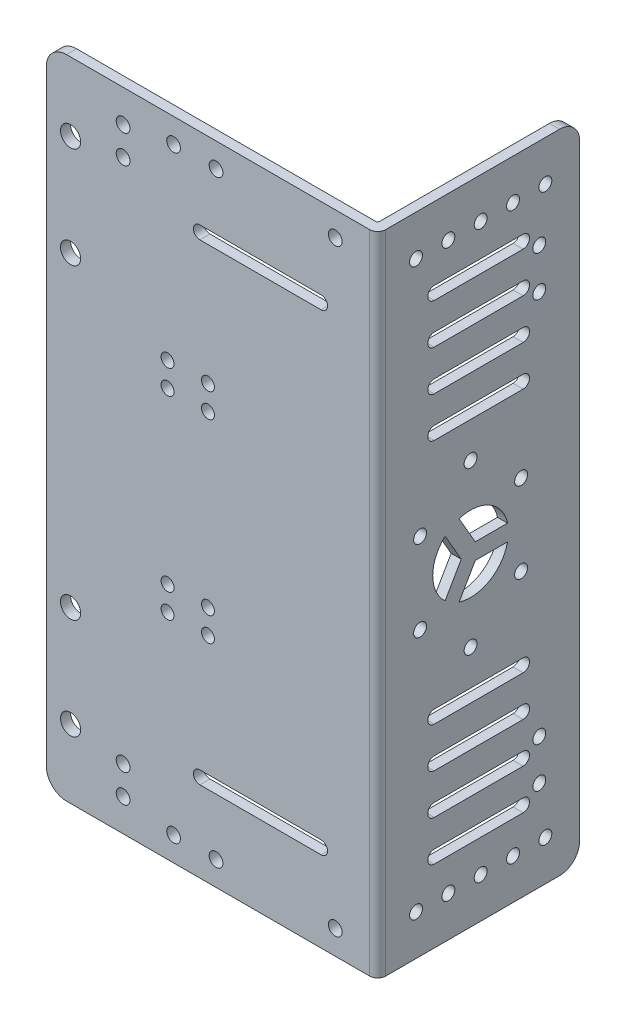
SolidWorks part; units mm, degrees
ref_plane "前视基准面" through (0, 0, 0) normal (0, 0, 1) x (1, 0, 0)
ref_plane "上视基准面" through (0, 0, 0) normal (0, 1, 0) x (1, 0, 0)
ref_plane "右视基准面" through (0, 0, 0) normal (1, 0, 0) x (0, 0, -1)
ref_plane "基准面4" through (0, 0, -50) normal (0, 0, -1) x (-1, 0, 0)
sketch "草图1" plane through (0, 0, -50) normal (0, 0, -1) x (-1, 0, 0)
  line L0 (-82, 0) -> (0, 0)
  line L1 (0, 0) -> (0, 160)
  line L2 (0, 160) -> (-82, 160)
  line L3 (-82, 160) -> (-82, 0)
extrude "凸台-拉伸1" add sketch "草图1" against normal blind 50
sketch "草图2" plane through (0, 160, 0) normal (0, 1, 0) x (-1, 0, 0)
  line L0 (0, -50) -> (0, -2.5)
  line L1 (0, -2.5) -> (-79.5, -2.5)
  line L2 (-79.5, -2.5) -> (-79.5, -50)
  line L3 (-79.5, -50) -> (0, -50)
extrude "切除-拉伸1" cut sketch "草图2" against normal through all
sketch "草图7" plane through (0, 0, -2.5) normal (0, 0, -1) x (-1, 0, 0)
  line L0 (-68, 20) -> (-38, 20)
  line L1 (-38, 23.2) -> (-68, 23.2)
  arc A0 (-68, 23.2) -> (-68, 20) centre (-68, 21.6) ccw
  arc A1 (-38, 20) -> (-38, 23.2) centre (-38, 21.6) ccw
extrude "切除-拉伸6" cut sketch "草图7" against normal through all
sketch "草图10" plane through (82, 0, 0) normal (1, 0, 0) x (0, 0, -1)
  line L0 (20.6906, 80) -> (16.6906, 86.9282)
  line L1 (16.6906, 73.0718) -> (20.6906, 80)
  arc A0 (16.6906, 86.9282) -> (16.6906, 73.0718) centre (23, 80) ccw
extrude "切除-拉伸9" cut sketch "草图10" against normal through all
sketch "草图11" plane through (82, 0, 0) normal (1, 0, 0) x (0, 0, -1)
  line L0 (20.1547, 88.9282) -> (24.1547, 82)
  line L1 (24.1547, 82) -> (32.1547, 82)
  arc A0 (32.1547, 82) -> (20.1547, 88.9282) centre (23, 80) ccw
extrude "切除-拉伸10" cut sketch "草图11" against normal through all
sketch "草图12" plane through (82, 0, 0) normal (1, 0, 0) x (0, 0, -1)
  line L0 (24.1547, 78) -> (20.1547, 71.0718)
  line L1 (32.1547, 78) -> (24.1547, 78)
  arc A0 (20.1547, 71.0718) -> (32.1547, 78) centre (23, 80) ccw
extrude "切除-拉伸11" cut sketch "草图12" against normal through all
sketch "草图13" plane through (82, 0, 0) normal (1, 0, 0) x (0, 0, -1)
  line L0 (36, 21.2) -> (14, 21.2)
  line L1 (14, 18) -> (36, 18)
  arc A0 (36, 18) -> (36, 21.2) centre (36, 19.6) ccw
  arc A1 (14, 21.2) -> (14, 18) centre (14, 19.6) ccw
extrude "切除-拉伸12" cut sketch "草图13" against normal through all
sketch "草图14" plane through (82, 0, 0) normal (1, 0, 0) x (0, 0, -1)
  line L0 (36, 31.2) -> (14, 31.2)
  line L1 (14, 28) -> (36, 28)
  arc A0 (36, 28) -> (36, 31.2) centre (36, 29.6) ccw
  arc A1 (14, 31.2) -> (14, 28) centre (14, 29.6) ccw
extrude "切除-拉伸13" cut sketch "草图14" against normal through all
sketch "草图15" plane through (82, 0, 0) normal (1, 0, 0) x (0, 0, -1)
  line L0 (36, 41.2) -> (14, 41.2)
  line L1 (14, 38) -> (36, 38)
  arc A0 (36, 38) -> (36, 41.2) centre (36, 39.6) ccw
  arc A1 (14, 41.2) -> (14, 38) centre (14, 39.6) ccw
extrude "切除-拉伸14" cut sketch "草图15" against normal through all
sketch "草图16" plane through (82, 0, 0) normal (1, 0, 0) x (0, 0, -1)
  line L0 (36, 51.2) -> (14, 51.2)
  line L1 (14, 48) -> (36, 48)
  arc A0 (36, 48) -> (36, 51.2) centre (36, 49.6) ccw
  arc A1 (14, 51.2) -> (14, 48) centre (14, 49.6) ccw
extrude "切除-拉伸15" cut sketch "草图16" against normal through all
sketch "草图17" plane through (82, 0, 0) normal (1, 0, 0) x (0, 0, -1)
  line L0 (36, 112) -> (14, 112)
  line L1 (14, 108.8) -> (36, 108.8)
  arc A0 (36, 108.8) -> (36, 112) centre (36, 110.4) ccw
  arc A1 (14, 112) -> (14, 108.8) centre (14, 110.4) ccw
extrude "切除-拉伸16" cut sketch "草图17" against normal through all
sketch "草图18" plane through (82, 0, 0) normal (1, 0, 0) x (0, 0, -1)
  line L0 (36, 122) -> (14, 122)
  line L1 (14, 118.8) -> (36, 118.8)
  arc A0 (36, 118.8) -> (36, 122) centre (36, 120.4) ccw
  arc A1 (14, 122) -> (14, 118.8) centre (14, 120.4) ccw
extrude "切除-拉伸17" cut sketch "草图18" against normal through all
sketch "草图19" plane through (82, 0, 0) normal (1, 0, 0) x (0, 0, -1)
  line L0 (36, 132) -> (14, 132)
  line L1 (14, 128.8) -> (36, 128.8)
  arc A0 (36, 128.8) -> (36, 132) centre (36, 130.4) ccw
  arc A1 (14, 132) -> (14, 128.8) centre (14, 130.4) ccw
extrude "切除-拉伸18" cut sketch "草图19" against normal through all
sketch "草图20" plane through (82, 0, 0) normal (1, 0, 0) x (0, 0, -1)
  line L0 (36, 142) -> (14, 142)
  line L1 (14, 138.8) -> (36, 138.8)
  arc A0 (36, 138.8) -> (36, 142) centre (36, 140.4) ccw
  arc A1 (14, 142) -> (14, 138.8) centre (14, 140.4) ccw
extrude "切除-拉伸19" cut sketch "草图20" against normal through all
sketch "草图21" plane through (0, 0, 0) normal (0, 0, 1) x (1, 0, 0)
  line L0 (68, 140) -> (38, 140)
  line L1 (38, 136.8) -> (68, 136.8)
  arc A0 (68, 136.8) -> (68, 140) centre (68, 138.4) ccw
  arc A1 (38, 140) -> (38, 136.8) centre (38, 138.4) ccw
extrude "切除-拉伸20" cut sketch "草图21" against normal through all
hole_wizard "Ø3.4 (3.4) 直径孔1" positions "草图25" profile "草图24" hole size "Ø3.4" standard "ANSI Metric"
sketch "草图25" plane through (0, 0, 0) normal (0, 0, 1) x (1, 0, 0)
  line L0 (82, 160) -> (82, 0) construction
  point P0 (31.5, 154)
  point P1 (42, 154)
  point P2 (71.5, 154)
  point P3 (71.5, 6)
  point P4 (42, 6)
  point P5 (31.5, 6)
  point P9 (19, 8)
  point P10 (19, 15)
  point P11 (19, 145)
  point P14 (19, 152)
  point P17 (0, 0)
  point P18 (0, 0)
  dimension "D1" = 40
  dimension "D2" = 40
  dimension "D3" = 10.5
  dimension "D4" = 10.5
  dimension "D5" = 10.5
  dimension "D6" = 10.5
sketch "草图24" plane through (31.5, 154, 0) normal (1, 0, 0) x (0, -1, 0)
  line L0 (0, 0) -> (0, 50)
  line L1 (0, 50) -> (1.7, 50)
  line L2 (1.7, 50) -> (1.7, 0)
  line L5 (1.7, 0) -> (0, 0)
  line L11 (0, -6.35) -> (0, 107.95) construction
  dimension "通孔孔直径" = 3.4
  dimension "通孔孔深度" = 50
hole_wizard "Ø3.2 (3.2) 直径孔2" positions "草图27" profile "草图26" hole size "Ø3.2" standard "ANSI Metric"
sketch "草图27" plane through (82, 0, 0) normal (1, 0, 0) x (0, 0, -1)
  point P0 (9.5, 150)
  point P1 (17.5, 150)
  point P2 (25.5, 150)
  point P3 (33.5, 150)
  point P4 (41.5, 150)
  point P5 (41.5, 10)
  point P6 (33.5, 10)
  point P7 (25.5, 10)
  point P8 (17.5, 10)
  point P9 (10.5, 90)
  point P10 (23, 100)
  point P11 (35.5, 90)
  point P12 (9.5, 10)
  point P13 (35.5, 70)
  point P14 (23, 60)
  point P15 (10.5, 70)
sketch "草图26" plane through (82, 150, -9.5) normal (0, 1, 0) x (0, 0, -1)
  line L0 (0, 0) -> (0, 82)
  line L1 (0, 82) -> (1.6, 82)
  line L2 (1.6, 82) -> (1.6, 0)
  line L5 (1.6, 0) -> (0, 0)
  line L11 (0, -6.35) -> (0, 107.95) construction
  dimension "通孔孔直径" = 3.2
  dimension "通孔孔深度" = 82
hole_wizard "Ø5.0 (5) 直径孔1" positions "草图29" profile "草图28" hole size "Ø5.0" standard "ANSI Metric"
sketch "草图29" plane through (0, 0, 0) normal (0, 0, 1) x (1, 0, 0)
  point P0 (6, 17)
  point P1 (6, 42)
  point P2 (6, 118)
  point P3 (6, 143)
sketch "草图28" plane through (6, 17, 0) normal (1, 0, 0) x (0, -1, 0)
  line L0 (0, 0) -> (0, 50)
  line L1 (0, 50) -> (2.5, 50)
  line L2 (2.5, 50) -> (2.5, 0)
  line L5 (2.5, 0) -> (0, 0)
  line L11 (0, -6.35) -> (0, 107.95) construction
  dimension "通孔孔直径" = 5
  dimension "通孔孔深度" = 50
fillet "圆角1" radius 0.5 1 edges at (79.5, 80, -2.5)
fillet "圆角2" radius 2 1 edges at (82, 80, 0)
fillet "圆角3" radius 5 4 edges at (80.75, 160, -50) (80.75, 0, -50) (0, 160, -1.25) (0, 0, -1.25)
sketch "草图30" plane through (0, 0, -2.5) normal (0, 0, -1) x (-1, 0, 0)
  line L0 (0, 80) -> (-142.596, 80) construction
  line L1 (0, 5) -> (0, 155) construction
  line L2 (-40, 59) -> (-40, 53) construction
  line L3 (-40, 53) -> (-40, 56) construction
  line L4 (-40, 56) -> (-17.627, 56) construction
  circle A0 centre (-40, 59) radius 1.6
  circle A1 centre (-40, 53) radius 1.6
  circle A2 centre (-30, 59) radius 1.6
  circle A3 centre (-30, 53) radius 1.6
  circle A4 centre (-40, 107) radius 1.6
  circle A5 centre (-30, 107) radius 1.6
  circle A6 centre (-30, 101) radius 1.6
  circle A7 centre (-40, 101) radius 1.6
  dimension "D1" = 3.2
  dimension "D2" = 3.2
  dimension "D3" = 6
  dimension "D4" = 3.2
  dimension "D6" = 21
  dimension "D5" = 10
  dimension "D7" = 30
extrude "切除-拉伸21" cut sketch "草图30" against normal blind 10
sketch "草图31" plane through (79.5, 0, 0) normal (-1, 0, 0) x (0, 0, 1)
  line L0 (-72.7837, 80) -> (48.2488, 80) construction
  line L1 (-3, 0) -> (-45, 0) construction
  line L2 (-3, 160) -> (-45, 160) construction
  line L3 (-40, 32.35) -> (-40, 22.35) construction
  line L4 (-50, 50) -> (-50, -50) construction
  line L5 (-40, 127.65) -> (-40, 137.65) construction
  circle A0 centre (-40, 32.35) radius 1.6
  circle A1 centre (-40, 22.35) radius 1.6
  circle A2 centre (-40, 137.65) radius 1.6
  circle A3 centre (-40, 127.65) radius 1.6
  dimension "D2" = 3.2
  dimension "D3" = 3.2
  dimension "D1" = 10
  dimension "D4" = 10
  dimension "D5" = 57.65
extrude "切除-拉伸22" cut sketch "草图31" against normal through all
